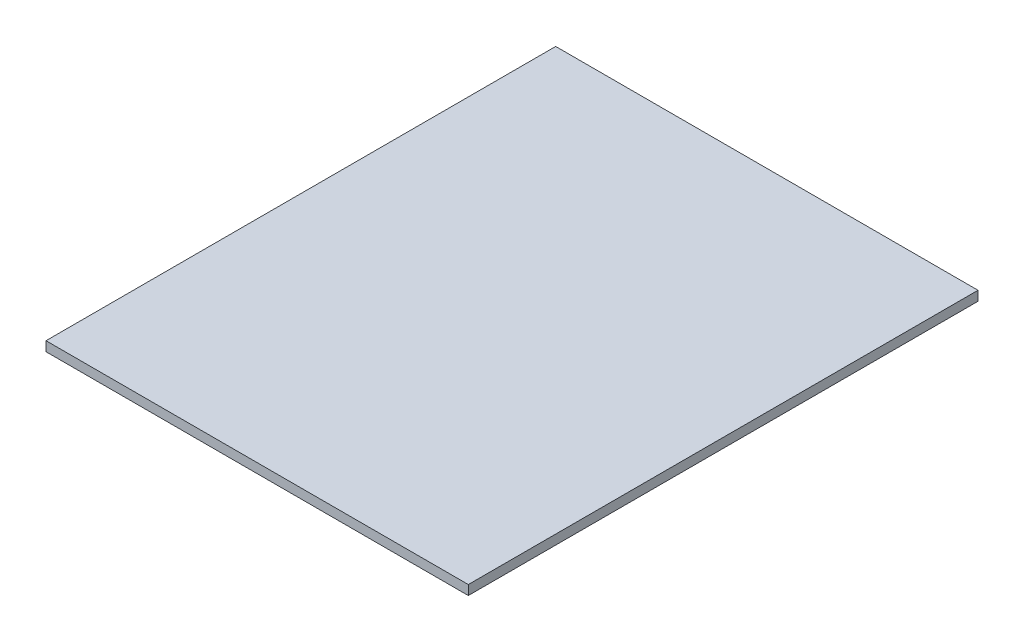
SolidWorks part; units mm, degrees
ref_plane "Front Plane" through (0, 0, 0) normal (0, 0, 1) x (1, 0, 0)
ref_plane "Top Plane" through (0, 0, 0) normal (0, 1, 0) x (1, 0, 0)
ref_plane "Right Plane" through (0, 0, 0) normal (1, 0, 0) x (0, 0, -1)
sketch "Sketch1" plane through (0, 0, 0) normal (0, 1, 0) x (1, 0, 0)
  line L1 (-22.2146, 13.8477) -> (21.9814, 13.8477)
  line L2 (-22.2146, 13.8477) -> (-22.2146, -39.4923)
  line L3 (-22.2146, -39.4923) -> (21.9814, -39.4923)
  line L4 (21.9814, 13.8477) -> (21.9814, -39.4923)
  dimension "D1" = 44.196
  dimension "D2" = 53.34
extrude "Boss-Extrude1" add sketch "Sketch1" along normal blind 1
